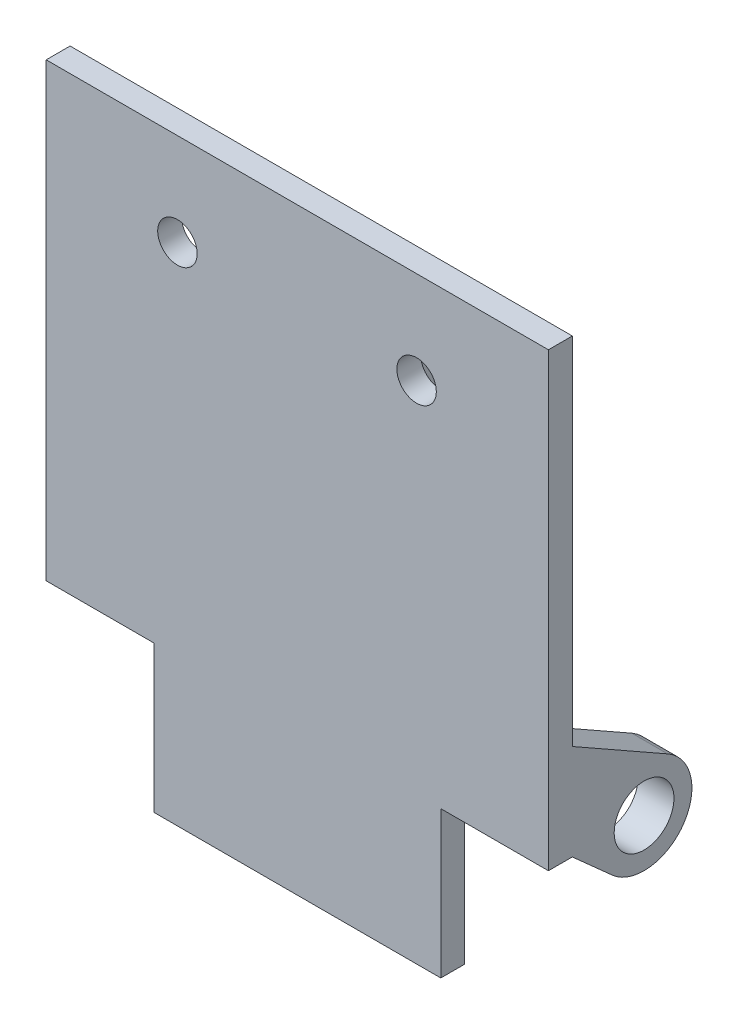
SolidWorks part; units mm, degrees
ref_plane "前视基准面" through (0, 0, 0) normal (0, 0, 1) x (1, 0, 0)
ref_plane "上视基准面" through (0, 0, 0) normal (0, 1, 0) x (1, 0, 0)
ref_plane "右视基准面" through (0, 0, 0) normal (1, 0, 0) x (0, 0, -1)
sketch "草图1" plane through (0, 0, 0) normal (0, 0, 1) x (1, 0, 0)
  line L1 (-21, 25) -> (21, 25)
  line L2 (-21, 25) -> (-21, -25)
  line L3 (-21, -25) -> (21, -25)
  line L4 (21, 25) -> (21, -25)
  line L5 (-21, 25) -> (21, -25) construction
  line L6 (-21, -25) -> (21, 25) construction
  point P0 (0, 0)
  dimension "D1" = 42
  dimension "D2" = 50
extrude "凸台-拉伸1" add sketch "草图1" along normal blind 2
sketch "草图3" plane through (0, 0, 0) normal (0, 0, -1) x (-1, 0, 0)
  line L0 (21, -25) -> (-21, -25) construction
  line L1 (5, -25) -> (2, -25)
  line L2 (5, -25) -> (5, -19)
  line L3 (5, -19) -> (2, -19)
  line L4 (2, -25) -> (2, -19)
  line L5 (21, 25) -> (21, -25) construction
  line L6 (5, 4) -> (2, 4)
  line L7 (5, 4) -> (5, 10)
  line L8 (5, 10) -> (2, 10)
  line L9 (2, 4) -> (2, 10)
  dimension "D1" = 16
  dimension "D2" = 6
  dimension "D3" = 23
  dimension "D4" = 6
  dimension "D5" = 3
extrude "凸台-拉伸2" add sketch "草图3" along normal blind 12
fillet "圆角1" radius 5 1 edges at (-2, 7, 0)
fillet "圆角2" radius 5 1 edges at (-2, -22, 0)
sketch "草图4" plane through (-5, 0, 0) normal (-1, 0, 0) x (0, 0, 1)
  line L0 (-12, -19) -> (0, -19) construction
  line L1 (-12, 4) -> (0, 4) construction
  line L3 (0, 25) -> (0, -25) construction
  circle A0 centre (-6.9, -20.6) radius 1
  circle A1 centre (-6.9, 6.3) radius 1
  dimension "D1" = 2
  dimension "D2" = 1.6
  dimension "D3" = 2.3
  dimension "D4" = 6.9
extrude "切除-拉伸1" cut sketch "草图4" against normal through all
sketch "草图5" plane through (21, 0, 0) normal (1, 0, 0) x (0, 0, -1)
  line L0 (0, -25) -> (0, 25) construction
  line L1 (0, -4.734) -> (0, -12.734)
  line L2 (0, -4.734) -> (7.9728, -9.2543)
  line L3 (0, -12.734) -> (3.3333, -15.7154)
  arc A0 (3.3333, -15.7154) -> (7.9728, -9.2543) centre (6, -12.734) ccw
  circle A1 centre (6, -12.734) radius 2.5
  dimension "D1" = 8
  dimension "D3" = 5
  dimension "D2" = 6
  dimension "D4" = 8
extrude "凸台-拉伸3" add sketch "草图5" against normal blind 3
sketch "草图6" plane through (0, 0, 0) normal (0, 0, -1) x (-1, 0, 0)
  line L0 (-21, -25) -> (-21, -12.734)
  line L1 (-21, -25) -> (-12, -25)
  line L2 (-21, -12.734) -> (-12, -12.734)
  line L3 (-12, -25) -> (-12, -12.734)
  line L4 (-21, -25) -> (-21, -12.734) construction
  line L6 (21, -25) -> (12, -25)
  line L7 (21, -25) -> (21, -12.734)
  line L8 (21, -12.734) -> (12, -12.734)
  line L9 (12, -25) -> (12, -12.734)
  dimension "D2" = 9
extrude "切除-拉伸2" cut sketch "草图6" against normal through all
sketch "草图7" plane through (0, 0, 2) normal (0, 0, 1) x (1, 0, 0)
  line L1 (-21, 17.266) -> (20.9516, 17.266) construction
  line L2 (-21, 25) -> (-21, -12.734) construction
  line L3 (12, -12.734) -> (21, -12.734) construction
  circle A0 centre (9.9758, 17.266) radius 1.65
  circle A1 centre (-10.0242, 17.266) radius 1.65
  point P2 (-0.0242, 17.266)
  point P11 (16.5, -12.734)
  dimension "D1" = 10
  dimension "D2" = 10
  dimension "D3" = 3.3
  dimension "D4" = 30
extrude "切除-拉伸3" cut sketch "草图7" against normal through all
fillet "圆角3" radius 3 1 edges at (-3.5, -25, -12)
